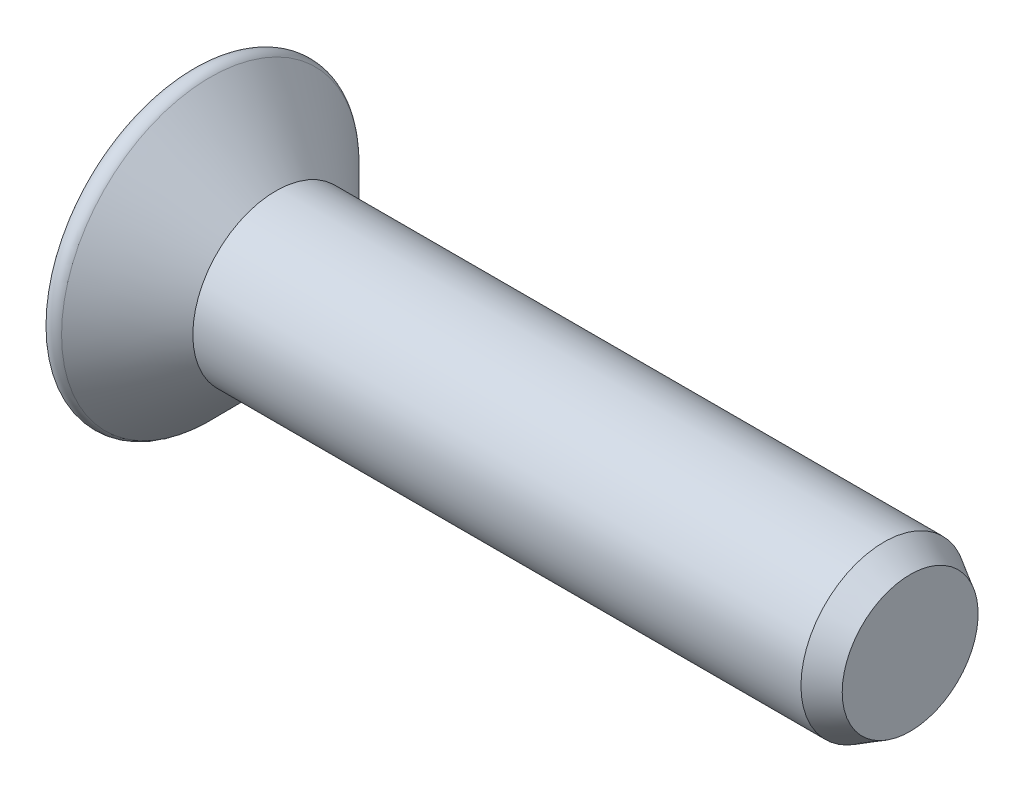
SolidWorks part; units mm, degrees
ref_plane "Front Plane" through (0, 0, 0) normal (0, 0, 1) x (1, 0, 0)
ref_plane "Top Plane" through (0, 0, 0) normal (0, 1, 0) x (1, 0, 0)
ref_plane "Right Plane" through (0, 0, 0) normal (1, 0, 0) x (0, 0, -1)
sketch "Sketch1" plane through (0, 0, 0) normal (0, 0, 1) x (1, 0, 0)
  line L0 (0, 0) -> (6.2784, 0) construction
  line L3 (-1.6, 0) -> (-1.6, -1.8061) construction
  line L4 (-1.6, 0) -> (8.4, 0)
  line L5 (0, 1.1) -> (8.4, 1.1)
  line L6 (8.4, 1.1) -> (8.4, 0)
  line L7 (0, 1.1) -> (-0.869, 1.969)
  arc A0 (-1.1, 1.9365) -> (-1.6, 0) centre (2.4, 0) ccw
  arc A1 (-1.1, 1.9365) -> (-0.869, 1.969) centre (-0.9723, 1.8658) cw
  dimension "rf" = 4
  dimension "d" = 2.2
  dimension "D1" = 45
  dimension "k" = 1.1
  dimension "f" = 0.5
  dimension "l" = 9.5
revolve "Revolve1" add sketch "Sketch1" angle 360 about L0
cosmetic thread "ThreadCosmetic" [suppressed] parameters "D1"=9.3, "D2"=1.65
chamfer "Chamfer1" distance 0.2 angle 60 1 edges at (8.4, 0, 1.1)
sketch "Sketch5" plane through (0, 0, 0) normal (0, 0, 1) x (1, 0, 0)
  line L0 (0.3703, 0.825) -> (0.2069, 0.825)
  line L1 (0.2069, 0.825) -> (0.0481, 1.1)
  line L2 (0.3703, 0.825) -> (0.529, 1.1)
  line L3 (0.0481, 1.1) -> (0.0481, 1.35)
  line L4 (0.529, 1.1) -> (0.529, 1.35)
  line L5 (0.0481, 1.35) -> (0.529, 1.35)
  line L6 (0.2886, 0.825) -> (0.2886, 0) construction
  line L7 (0, 0) -> (7.3035, 0) construction
  line L9 (0, 1.1) -> (0, -1.1) construction
  line L12 (8.0536, 1.1) -> (0, 1.1) construction
  dimension "D2" = 60
  dimension "D3" = 0.25
  dimension "advance" = 0.4809
  dimension "minordia" = 1.65
  dimension "threadstart" = 0.2886
revolve "ThreadSchematic" [suppressed] cut sketch "Sketch5" angle 360 about L7
pattern_linear "ThdSchPat" [suppressed] count 18 spacing 0.4809 along (1, 0, 0)
sketch "Sketch2" plane through (0, 0, 0) normal (0, 0, 1) x (1, 0, 0)
  line L0 (0, 0) -> (5.7679, 0) construction
  line L1 (8.4, 0) -> (6.4947, 1.1)
  line L2 (8.4, 1.1) -> (8.4, 0) construction
  line L4 (6.4947, 1.1) -> (6.4947, 1.2)
  line L5 (6.4947, 1.2) -> (8.5, 1.2)
  line L6 (8.5, 1.2) -> (8.5, 0)
  line L7 (8.5, 0) -> (8.4, 0)
  point P5 (0, 1.1)
  dimension "D1" = 30
  dimension "D2" = 0.1
  dimension "D3" = 0.1
revolve "EndCone" [suppressed] cut sketch "Sketch2" angle 360 about L0
ref_plane "Plane4" through (-1.6, 0, 0) normal (1, 0, 0) x (0, 0, -1)
sketch "Sketch3" plane through (-1.6, 0, 0) normal (1, 0, 0) x (0, 0, -1)
  line L0 (0, 2.343) -> (0, -2.4842) construction
  line L1 (2.7661, 0) -> (-3.4558, 0) construction
  line L2 (-0.22, 1.1) -> (0.22, 1.1)
  line L3 (0.22, 1.1) -> (0.1467, 0.7333)
  line L4 (0, 0) -> (1.9578, 1.9578) construction
  line L5 (0.1467, 0.7333) -> (0.3614, 0.3614)
  line L6 (0.1467, 0.7333) -> (0, 0) construction
  line L7 (-0.1467, 0.7333) -> (-0.3614, 0.3614)
  line L8 (-0.22, 1.1) -> (-0.1467, 0.7333)
  line L9 (1.1, 0.22) -> (1.1, -0.22)
  line L10 (1.1, -0.22) -> (0.7333, -0.1467)
  line L11 (0.7333, -0.1467) -> (0.3614, -0.3614)
  line L12 (0.7333, 0.1467) -> (0.3614, 0.3614)
  line L13 (1.1, 0.22) -> (0.7333, 0.1467)
  line L14 (0.22, -1.1) -> (-0.22, -1.1)
  line L15 (-0.22, -1.1) -> (-0.1467, -0.7333)
  line L16 (-0.1467, -0.7333) -> (-0.3614, -0.3614)
  line L17 (0.1467, -0.7333) -> (0.3614, -0.3614)
  line L18 (0.22, -1.1) -> (0.1467, -0.7333)
  line L19 (-1.1, -0.22) -> (-1.1, 0.22)
  line L20 (-1.1, 0.22) -> (-0.7333, 0.1467)
  line L21 (-0.7333, 0.1467) -> (-0.3614, 0.3614)
  line L22 (-0.7333, -0.1467) -> (-0.3614, -0.3614)
  line L23 (-1.1, -0.22) -> (-0.7333, -0.1467)
  point P14 (0, 1.1)
  point P23 (1.1, 0)
  point P30 (0, -1.1)
  point P37 (-1.1, 0)
  dimension "D1" = 45
  dimension "m" = 2.2
  dimension "D3" = 0.44
  dimension "D4" = 75
  dimension "D5" = 1.4667
extrude "Cut-Extrude1" cut sketch "Sketch3" along normal blind 0.8 draft 6
sketch "Sketch4" plane through (-1.6, 0, 0) normal (1, 0, 0) x (0, 0, -1)
  line L0 (0, 2.1951) -> (0, -2.1951) construction
  line L1 (2.1996, 0) -> (-2.3835, 0) construction
  line L2 (-0.9723, -0.9723) -> (0.9723, 0.9723) construction
  line L3 (1.1, 0.275) -> (-1.1, 0.275)
  line L4 (1.1, 0.275) -> (1.1, -0.275)
  line L5 (1.1, -0.275) -> (-1.1, -0.275)
  line L6 (-1.1, 0.275) -> (-1.1, -0.275)
  line L7 (0.275, 1.1) -> (-0.275, 1.1)
  line L8 (0.275, 1.1) -> (0.275, -1.1)
  line L9 (0.275, -1.1) -> (-0.275, -1.1)
  line L10 (-0.275, 1.1) -> (-0.275, -1.1)
  line L11 (0.9723, 0.9723) -> (0.4468, 0.275)
  line L12 (0.9723, 0.9723) -> (0.275, 0.4468)
  line L13 (0.275, 0.4468) -> (-0.275, 0.4468) construction
  line L14 (0, 0) -> (-0.9723, 0.9723) construction
  line L15 (-0.9723, -0.9723) -> (-0.275, -0.4468)
  line L16 (-0.9723, -0.9723) -> (-0.4468, -0.275)
  line L17 (-0.275, 0.4468) -> (-0.9723, 0.9723)
  line L18 (-0.9723, 0.9723) -> (-0.4468, 0.275)
  line L19 (-0.4468, -0.275) -> (-0.4468, 0.275) construction
  line L20 (0.4468, -0.275) -> (0.9723, -0.9723)
  line L21 (0.9723, -0.9723) -> (0.275, -0.4468)
  circle A0 centre (0, 0) radius 1.375 construction
  dimension "m" = 2.2
  dimension "D1" = 2.75
  dimension "D2" = 0.55
  dimension "D3" = 45
  dimension "D4" = 8
  dimension "D5" = 45
extrude "TypeZ" [suppressed] cut sketch "Sketch4" along normal blind 0.8
equation "\"D1@ThreadCosmetic\" = \"l@Sketch1\" - \"D1@Chamfer1\""
equation "\"minordia@Sketch5\" = \"D2@ThreadCosmetic\""
equation "\"D1@Plane4\" = \"k@Sketch1\" + \"f@Sketch1\""
equation "\"D5@Sketch3\" = \"m@Sketch3\" * 2 / 3"
equation "\"D3@Sketch3\" = \"m@Sketch3\" / 5"
equation "\"D1@Cut-Extrude1\" =  ( \"k@Sketch1\" + \"f@Sketch1\" )  / 2"
equation "\"D2@Sketch4\" =  \"m@Sketch4\" / 4"
equation "\"D1@TypeZ\" =  ( \"k@Sketch1\" + \"f@Sketch1\" )  / 2"
equation "\"D1@Sketch4\" = \"m@Sketch4\" * 5 / 4"
equation "\"m@Sketch4\" = \"m@Sketch3\""
equation "\"threadstart@Sketch5\" = \"advance@Sketch5\"*0.6"
equation "\"D1@ThdSchPat\" = int(((\"l@Sketch1\"-\"k@Sketch1\")/\"advance@Sketch5\") + 0.999)"
equation "\"D3@ThdSchPat\" = \"advance@Sketch5\""
